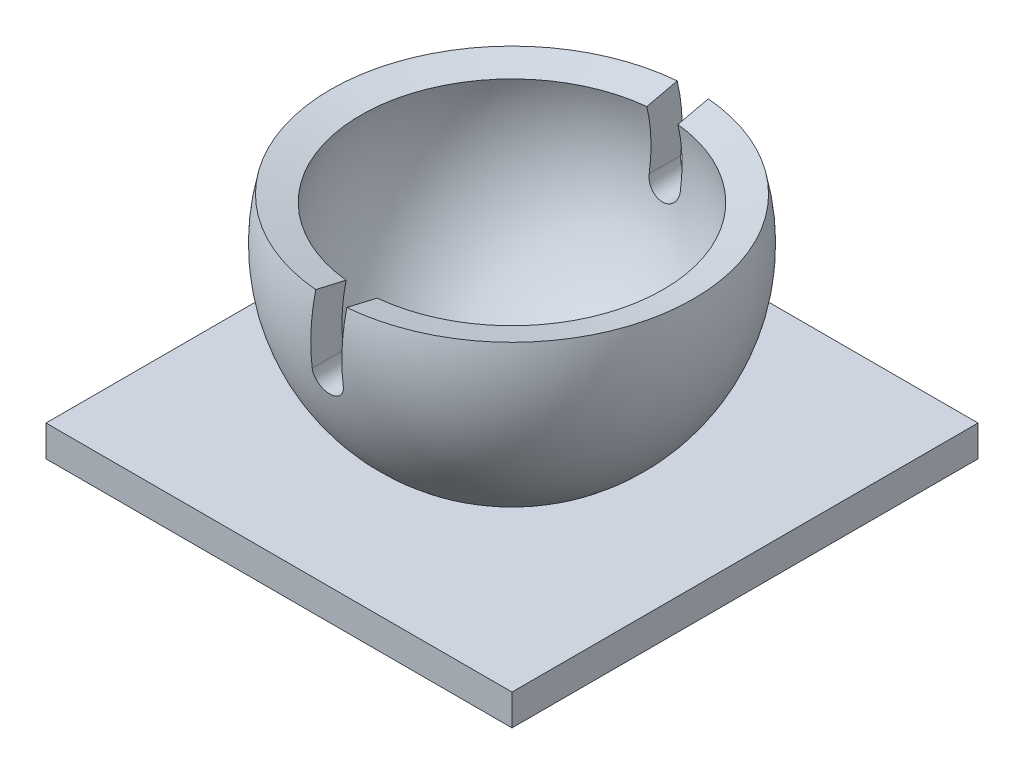
SolidWorks part; units mm, degrees
ref_plane "Front Plane" through (0, 0, 0) normal (0, 0, 1) x (1, 0, 0)
ref_plane "Top Plane" through (0, 0, 0) normal (0, 1, 0) x (1, 0, 0)
ref_plane "Right Plane" through (0, 0, 0) normal (1, 0, 0) x (0, 0, -1)
sketch "Sketch1" plane through (0, 0, 0) normal (0, 0, 1) x (1, 0, 0)
  line L0 (0, 16.649) -> (0, -23.351) construction
  line L2 (0, -23.351) -> (0, -27.351)
  line L4 (19.4622, 1.2557) -> (23.3582, 2.1622)
  arc A0 (19.4622, 1.2557) -> (0, -23.351) centre (0, -3.351) cw
  arc A1 (0, -27.351) -> (23.3582, 2.1622) centre (0, -3.351) ccw
  point P7 (19.4863, 1.2413)
  dimension "D4" = 24
  dimension "D5" = 20
  dimension "D1" = 40
  dimension "D3" = 4
revolve "Revolve1" add sketch "Sketch1" angle 360 about L0
sketch "Sketch2" plane through (0, 0, 0) normal (0, 0, 1) x (1, 0, 0)
  line L0 (0, 13.6196) -> (-2, 13.6196)
  line L1 (-16.9706, 13.6196) -> (16.9706, 13.6196) construction
  line L2 (-2, 13.6196) -> (-2, -6.3804)
  line L4 (2, -6.3804) -> (2, 13.6196)
  line L5 (2, 13.6196) -> (0, 13.6196)
  arc A0 (-2, -6.3804) -> (2, -6.3804) centre (0, -6.3804) ccw
  dimension "D1" = 2
  dimension "D2" = 20
  dimension "D3" = 4
extrude "Cut-Extrude1" cut sketch "Sketch2" against normal through all both and the other way through all
ref_plane "Plane1" through (0, -27.351, 0) normal (0, -1, 0) x (-1, 0, 0)
sketch "Sketch4" plane through (0, -27.351, 0) normal (0, -1, 0) x (-1, 0, 0)
  line L1 (30, 30) -> (-30, 30)
  line L2 (30, 30) -> (30, -30)
  line L3 (30, -30) -> (-30, -30)
  line L4 (-30, 30) -> (-30, -30)
  line L5 (30, 30) -> (-30, -30) construction
  line L6 (30, -30) -> (-30, 30) construction
  point P0 (0, 0)
  dimension "D1" = 60
  dimension "D2" = 60
extrude "Boss-Extrude1" add sketch "Sketch4" against normal blind 4
